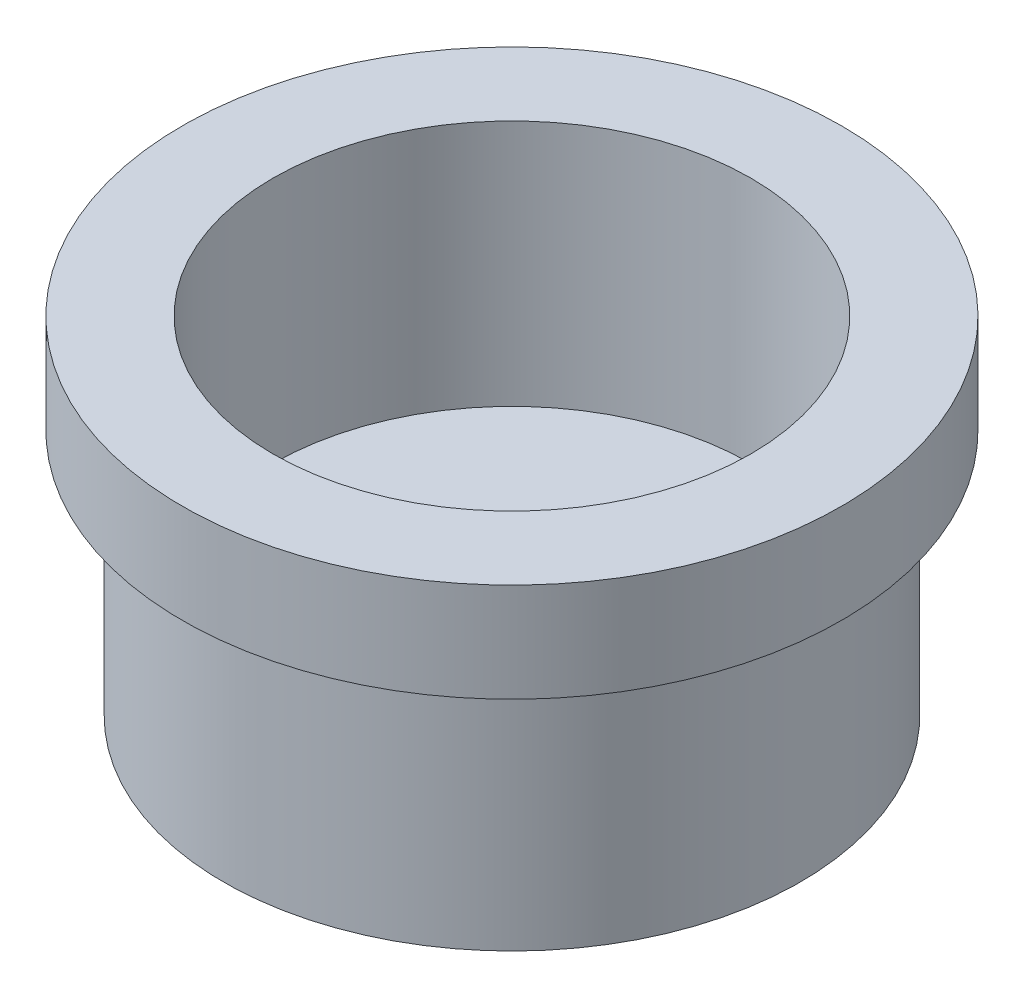
SolidWorks part; units mm, degrees
ref_plane "前视基准面" through (0, 0, 0) normal (0, 0, 1) x (1, 0, 0)
ref_plane "上视基准面" through (0, 0, 0) normal (0, 1, 0) x (1, 0, 0)
ref_plane "右视基准面" through (0, 0, 0) normal (1, 0, 0) x (0, 0, -1)
other "Configuration Table"
sketch "草图1" plane through (0, 0, 0) normal (0, 0, 1) x (1, 0, 0)
  line L0 (0, 0) -> (-2.5, 0) construction
  line L1 (-2.5, 0) -> (-2.5, 9)
  line L2 (-2.5, 9) -> (-4.75, 9)
  line L3 (-4.75, 9) -> (-4.75, 13)
  line L4 (-4.75, 13) -> (-14.5, 13)
  line L5 (-14.5, 13) -> (-14.5, 28)
  line L6 (-14.5, 28) -> (-20, 28)
  line L7 (-20, 28) -> (-20, 22)
  line L8 (-20, 22) -> (-17.5, 22)
  line L9 (-17.5, 22) -> (-17.5, 7)
  line L10 (-17.5, 7) -> (-6.5, 7)
  line L11 (-6.5, 7) -> (-6.5, 6)
  line L12 (-6.5, 6) -> (-4.5, 6)
  line L13 (-4.5, 6) -> (-4.5, 0)
  line L14 (-4.5, 0) -> (-2.5, 0)
  line L15 (0, 0) -> (0, 17.2894) construction
  dimension "D1" = 5
  dimension "D2" = 9
  dimension "D3" = 2
  dimension "D4" = 9.5
  dimension "D5" = 6
  dimension "D6" = 4
  dimension "D7" = 3
  dimension "D8" = 29
  dimension "D9" = 15
  dimension "D10" = 40
  dimension "D11" = 35
  dimension "D12" = 6
  dimension "D13" = 1
revolve "旋转1" add sketch "草图1" angle 360 about L15
